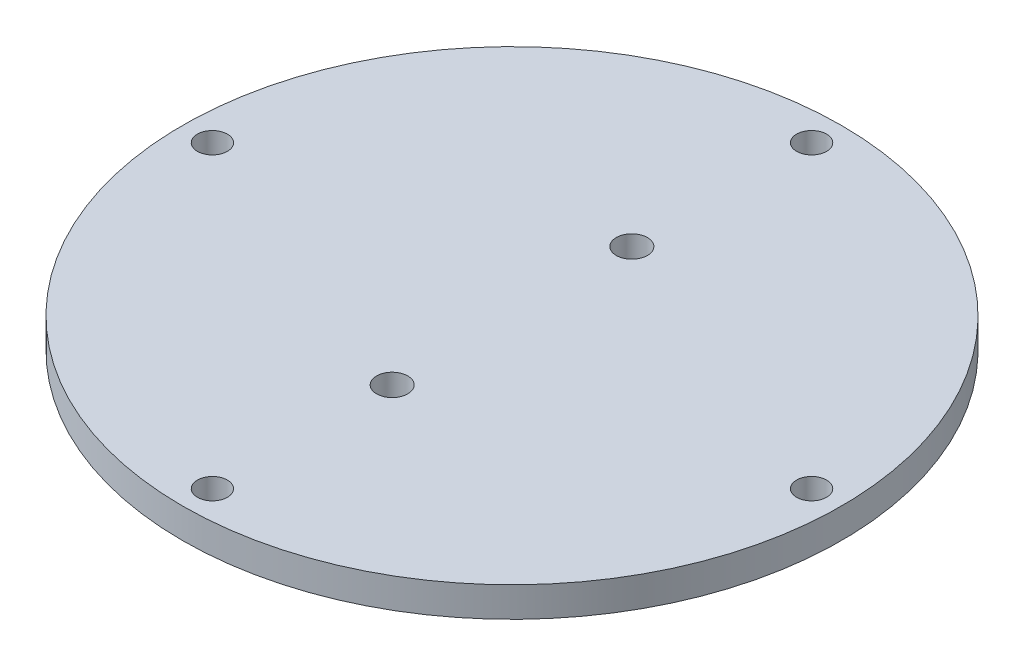
SolidWorks part; units mm, degrees
ref_plane "Front Plane" through (0, 0, 0) normal (0, 0, 1) x (1, 0, 0)
ref_plane "Top Plane" through (0, 0, 0) normal (0, 1, 0) x (1, 0, 0)
ref_plane "Right Plane" through (0, 0, 0) normal (1, 0, 0) x (0, 0, -1)
sketch "Sketch1" plane through (0, 0, 0) normal (0, 1, 0) x (1, 0, 0)
  line L0 (0, 0) -> (45, 0) construction
  circle A0 centre (0, 0) radius 45 construction
  circle A1 centre (0, 0) radius 55
  circle A2 centre (0, 20) radius 2.6
  circle A3 centre (0, -20) radius 2.6
  circle A4 centre (0, 50) radius 2.5
  circle A5 centre (50, 0) radius 2.5
  circle A6 centre (0, -50) radius 2.5
  circle A7 centre (-50, 0) radius 2.5
  point P20 (0, 0)
  dimension "D1" = 90
  dimension "D2" = 5.2
  dimension "D4" = 110
  dimension "D5" = 5
  dimension "D3" = 20
  dimension "D6" = 4
  dimension "8.5" = 50
extrude "Boss-Extrude1" add sketch "Sketch1" along normal blind 5
